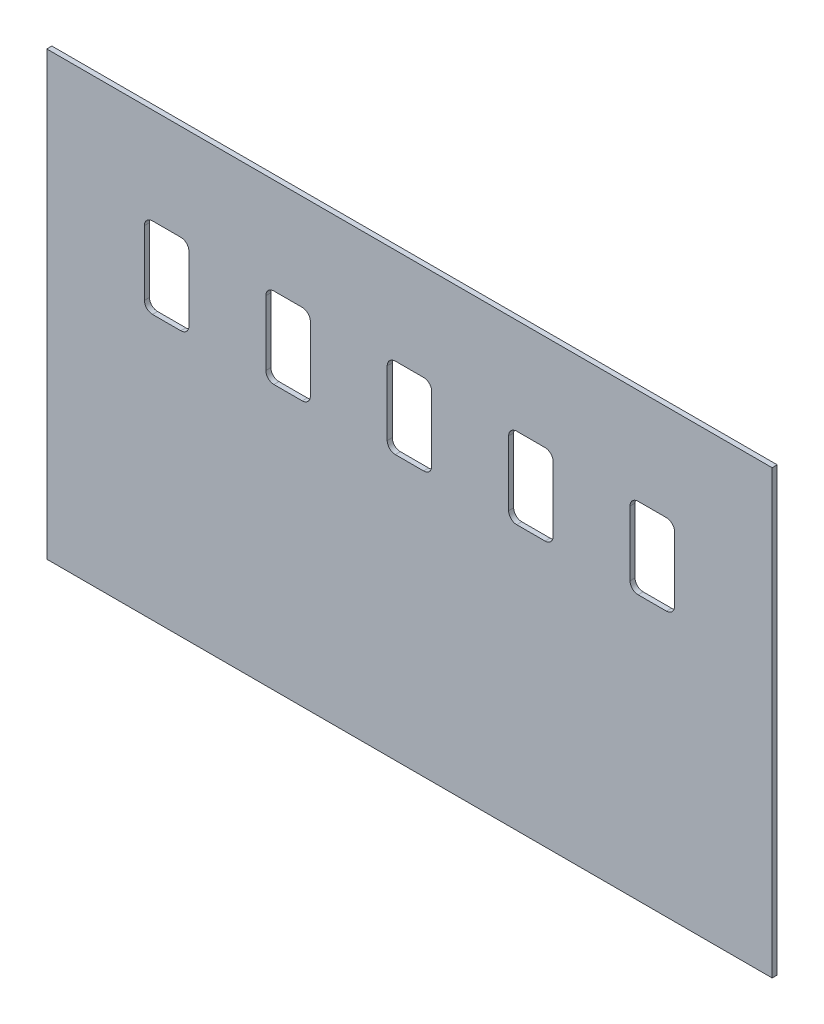
SolidWorks part; units mm, degrees
ref_plane "Front Plane" through (0, 0, 0) normal (0, 0, 1) x (1, 0, 0)
ref_plane "Top Plane" through (0, 0, 0) normal (0, 1, 0) x (1, 0, 0)
ref_plane "Right Plane" through (0, 0, 0) normal (1, 0, 0) x (0, 0, -1)
sketch "Sketch1" plane through (0, 0, 0) normal (0, 0, 1) x (1, 0, 0)
  line L1 (-227.6475, -138.684) -> (227.6475, -138.684)
  line L2 (-227.6475, -138.684) -> (-227.6475, 138.684)
  line L3 (-227.6475, 138.684) -> (227.6475, 138.684)
  line L4 (227.6475, -138.684) -> (227.6475, 138.684)
  line L5 (0, 138.684) -> (0, -138.684) construction
  line L6 (-227.6475, 0) -> (227.6475, 0) construction
  point P0 (0, 0)
  point P4 (-159.0675, 0)
  point P5 (159.0675, 0)
  point P6 (0, 97.0788)
  point P7 (0, -97.0788)
  dimension "Width" = 277.368
  dimension "Break" = 68.58
  dimension "D2" = 68.58
  dimension "D1" = 41.6052
  dimension "D3" = 41.6052
  dimension "D4" = 455.295
sketch "Sketch2" plane through (0, 0, 0) normal (1, 0, 0) x (0, 0, -1)
  line L0 (-1.5875, -138.684) -> (1.5875, -138.684)
  dimension "Thickness" = 3.175
sketch "Sketch3" plane through (0, 0, 0) normal (0, 0, 1) x (1, 0, 0)
  line L0 (-227.6475, -138.684) -> (-227.6475, 138.684) construction
  line L1 (-227.6475, -138.684) -> (227.6475, -138.684) construction
  line L2 (227.6475, -138.684) -> (227.6475, 138.684) construction
  line L3 (-227.6475, 138.684) -> (227.6475, 138.684) construction
  line L4 (-227.6475, -138.684) -> (-227.6475, 138.684)
  line L5 (-227.6475, -138.684) -> (227.6475, -138.684)
  line L6 (227.6475, -138.684) -> (227.6475, 138.684)
  line L7 (-227.6475, 138.684) -> (227.6475, 138.684)
extrude "Boss-Extrude1" add sketch "Sketch3" along normal mid plane 3.175
sketch "Sketch4" plane through (0, 0, 1.5875) normal (0, 0, 1) x (1, 0, 0)
  line L0 (-227.6475, 52.959) -> (-158.75, 52.959) construction
  line L1 (-82.55, 52.959) -> (-82.55, 78.359) construction
  line L2 (-82.55, 78.359) -> (-90.17, 78.359) construction
  line L3 (-158.75, 52.959) -> (-158.75, 78.359) construction
  line L6 (-227.6475, -105.791) -> (-227.6475, 52.959) construction
  line L7 (-227.6475, -115.316) -> (-227.6475, 138.684) construction
  line L8 (-158.75, 52.959) -> (-82.55, 52.959) construction
  line L9 (-82.55, 52.959) -> (-6.35, 52.959) construction
  line L10 (-6.35, 52.959) -> (69.85, 52.959) construction
  line L11 (69.85, 52.959) -> (146.05, 52.959) construction
  line L12 (-82.55, 52.959) -> (-82.55, 27.559) construction
  line L13 (-82.55, 27.559) -> (-62.23, 27.559) construction
  line L16 (-158.75, 78.359) -> (-166.37, 78.359) construction
  line L17 (-158.75, 52.959) -> (-158.75, 27.559) construction
  line L18 (-158.75, 27.559) -> (-138.43, 27.559) construction
  line L19 (-6.35, 52.959) -> (-6.35, 78.359) construction
  line L20 (-161.29, 78.359) -> (-143.51, 78.359)
  line L21 (-166.37, 73.279) -> (-166.37, 32.639)
  line L22 (-161.29, 27.559) -> (-143.51, 27.559)
  line L23 (-138.43, 73.279) -> (-138.43, 32.639)
  line L24 (-6.35, 78.359) -> (-13.97, 78.359) construction
  line L25 (-6.35, 52.959) -> (-6.35, 27.559) construction
  line L26 (-6.35, 27.559) -> (13.97, 27.559) construction
  line L27 (69.85, 52.959) -> (69.85, 78.359) construction
  line L28 (-8.89, 78.359) -> (8.89, 78.359)
  line L29 (-13.97, 73.279) -> (-13.97, 32.639)
  line L30 (-8.89, 27.559) -> (8.89, 27.559)
  line L31 (13.97, 73.279) -> (13.97, 32.639)
  line L32 (69.85, 78.359) -> (62.23, 78.359) construction
  line L33 (69.85, 52.959) -> (69.85, 27.559) construction
  line L34 (69.85, 27.559) -> (90.17, 27.559) construction
  line L35 (146.05, 52.959) -> (146.05, 78.359) construction
  line L36 (67.31, 78.359) -> (85.09, 78.359)
  line L37 (62.23, 73.279) -> (62.23, 32.639)
  line L38 (67.31, 27.559) -> (85.09, 27.559)
  line L39 (90.17, 73.279) -> (90.17, 32.639)
  line L40 (146.05, 78.359) -> (138.43, 78.359) construction
  line L41 (146.05, 52.959) -> (146.05, 27.559) construction
  line L42 (146.05, 27.559) -> (166.37, 27.559) construction
  line L44 (143.51, 78.359) -> (161.29, 78.359)
  line L45 (138.43, 73.279) -> (138.43, 32.639)
  line L46 (143.51, 27.559) -> (161.29, 27.559)
  line L47 (166.37, 73.279) -> (166.37, 32.639)
  line L48 (-85.09, 78.359) -> (-67.31, 78.359)
  line L49 (-90.17, 73.279) -> (-90.17, 32.639)
  line L50 (-85.09, 27.559) -> (-67.31, 27.559)
  line L51 (-62.23, 73.279) -> (-62.23, 32.639)
  arc A0 (138.43, 32.639) -> (143.51, 27.559) centre (143.51, 32.639) ccw
  arc A1 (166.37, 32.639) -> (161.29, 27.559) centre (161.29, 32.639) cw
  arc A2 (161.29, 78.359) -> (166.37, 73.279) centre (161.29, 73.279) cw
  arc A3 (138.43, 73.279) -> (143.51, 78.359) centre (143.51, 73.279) cw
  arc A4 (62.23, 32.639) -> (67.31, 27.559) centre (67.31, 32.639) ccw
  arc A5 (90.17, 32.639) -> (85.09, 27.559) centre (85.09, 32.639) cw
  arc A6 (85.09, 78.359) -> (90.17, 73.279) centre (85.09, 73.279) cw
  arc A7 (67.31, 78.359) -> (62.23, 73.279) centre (67.31, 73.279) ccw
  arc A8 (-13.97, 32.639) -> (-8.89, 27.559) centre (-8.89, 32.639) ccw
  arc A9 (13.97, 32.639) -> (8.89, 27.559) centre (8.89, 32.639) cw
  arc A10 (8.89, 78.359) -> (13.97, 73.279) centre (8.89, 73.279) cw
  arc A11 (-8.89, 78.359) -> (-13.97, 73.279) centre (-8.89, 73.279) ccw
  arc A15 (-138.43, 32.639) -> (-143.51, 27.559) centre (-143.51, 32.639) cw
  arc A16 (-143.51, 78.359) -> (-138.43, 73.279) centre (-143.51, 73.279) cw
  arc A17 (-166.37, 73.279) -> (-161.29, 78.359) centre (-161.29, 73.279) cw
  arc A18 (-166.37, 32.639) -> (-161.29, 27.559) centre (-161.29, 32.639) ccw
  arc A19 (-90.17, 32.639) -> (-85.09, 27.559) centre (-85.09, 32.639) ccw
  arc A20 (-62.23, 32.639) -> (-67.31, 27.559) centre (-67.31, 32.639) cw
  arc A21 (-67.31, 78.359) -> (-62.23, 73.279) centre (-67.31, 73.279) cw
  arc A22 (-85.09, 78.359) -> (-90.17, 73.279) centre (-85.09, 73.279) ccw
  point P14 (-152.4, 78.359)
  point P16 (-76.2, 78.359)
  point P17 (-90.17, 52.959)
  point P18 (-13.97, 52.959)
  point P95 (62.23, 52.959)
  point P96 (138.43, 52.959)
  point P97 (0, 78.359)
  point P98 (76.2, 78.359)
  point P99 (152.4, 78.359)
  point P107 (-166.37, 52.959)
  dimension "D1" = 5.08
  dimension "D2" = 5.08
  dimension "D8" = 27.94
  dimension "D9" = 27.94
  dimension "D10" = 27.94
  dimension "D11" = 27.94
  dimension "D12" = 27.94
  dimension "D3" = 76.2
  dimension "D4" = 76.2
  dimension "D5" = 152.4
  dimension "D6" = 152.4
extrude "Cut-Extrude1" cut sketch "Sketch4" against normal blind 25.4 contours L21 A18 L22 A15 L23 A16 L20 A17 | A22 L48 A21 L51 A20 L50 A19 L49 | L29 A8 L30 A9 L31 A10 L28 A11 | L37 A4 L38 A5 L39 A6 L36 A7 | A3 L44 A2 L47 A1 L46 A0 L45
equation "\"D1@Boss-Extrude1\" = \"Thickness@Sketch2\""
equation "\"D2@Sketch1\" = \"Break@Sketch1\""
equation "\"D1@Sketch1\"=\"Width@Sketch1\"*0.15"
equation "\"D3@Sketch1\"=\"D1@Sketch1\""
equation "\"SlotWidth\"= 1.1in"
equation "\"D8@Sketch4\"=\"SlotWidth\""
equation "\"D9@Sketch4\"=\"SlotWidth\""
equation "\"D10@Sketch4\"=\"SlotWidth\""
equation "\"D11@Sketch4\"=\"SlotWidth\""
equation "\"D12@Sketch4\"=\"SlotWidth\""
